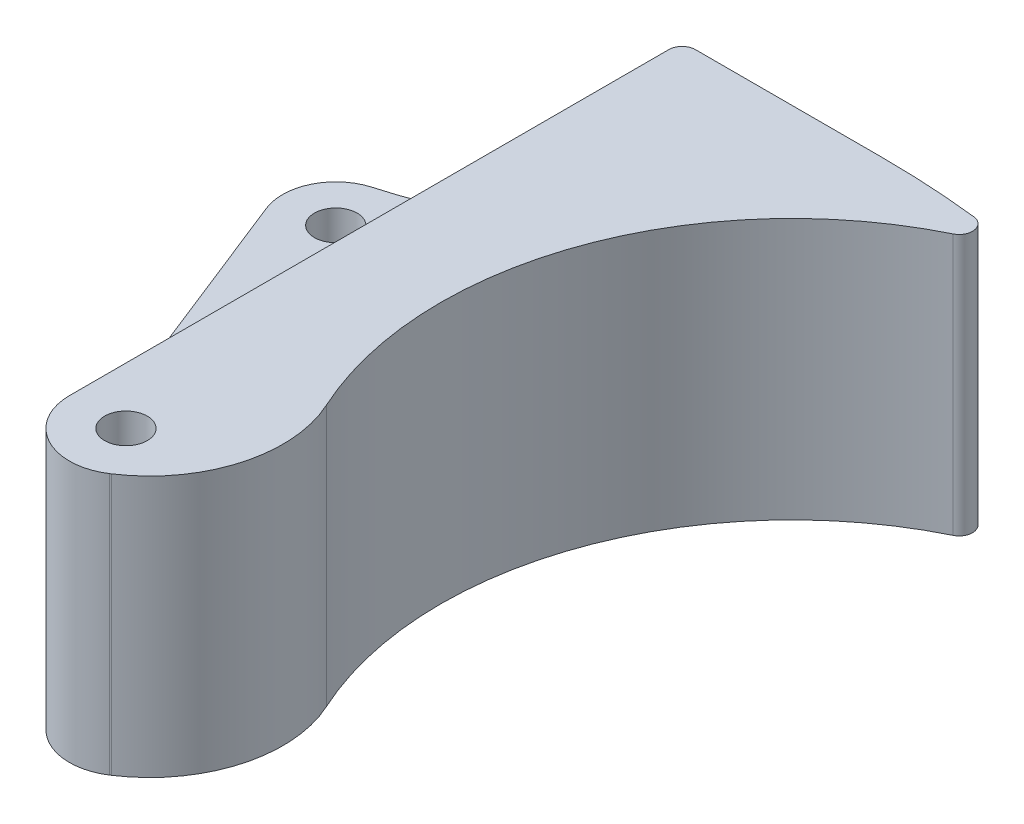
SolidWorks part; units mm, degrees
ref_plane "Front Plane" through (0, 0, 0) normal (0, 0, 1) x (1, 0, 0)
ref_plane "Top Plane" through (0, 0, 0) normal (0, 1, 0) x (1, 0, 0)
ref_plane "Right Plane" through (0, 0, 0) normal (1, 0, 0) x (0, 0, -1)
sketch "Sketch1" plane through (0, 0, 0) normal (0, 1, 0) x (1, 0, 0)
  line L3 (2.9609, -4.5129) -> (13.6525, 2.502)
  line L4 (-5.3975, 58.42) -> (13.6525, 58.42)
  line L6 (-5.3975, 58.42) -> (-5.3975, 0)
  circle A0 centre (0, 0) radius 2.032
  arc A2 (-5.3975, 0) -> (2.9609, -4.5129) centre (0, 0) ccw
  arc A4 (27.6225, 57.2154) -> (13.6525, 58.42) centre (13.6525, -23.19) ccw
  arc A5 (27.6225, 57.2154) -> (13.6525, 2.502) centre (38.1, 25.4) ccw
  dimension "D1" = 66.9925
  dimension "D2" = 4.064
  dimension "D3" = 10.795
  dimension "D4" = 13.97
  dimension "D5" = 58.42
  dimension "D6" = 38.1
  dimension "D7" = 25.4
  dimension "D9" = 19.05
extrude "Boss-Extrude1" add sketch "Sketch1" along normal mid plane 24.892
fillet "Fillet2" radius 12.7 1 edges at (13.6525, 0, -2.502)
sketch "Sketch2" plane through (0, 0, 0) normal (0, 1, 0) x (1, 0, 0)
  line L0 (-5.3975, 40.64) -> (-14.4921, 37.8813)
  line L1 (-5.3975, 58.42) -> (-5.3975, 0) construction
  line L2 (-5.3975, 0) -> (-17.7402, 31.1486)
  line L4 (-5.3975, 40.64) -> (-5.3975, 0)
  arc A0 (-14.4921, 37.8813) -> (-17.7402, 31.1486) centre (-13.0175, 33.02) ccw
  circle A1 centre (-13.0175, 33.02) radius 2.032
  dimension "D1" = 4.064
  dimension "D2" = 5.08
  dimension "D3" = 40.64
  dimension "D4" = 7.62
  dimension "D5" = 7.62
extrude "Boss-Extrude2" add sketch "Sketch2" along normal mid plane 12.3825
fillet "Fillet7" radius 10.16 1 edges at (-5.3975, 0, -40.64)
sketch "Sketch5" [suppressed] plane through (0, 0, -57.15) normal (0, 0, -1) x (-1, 0, 0)
  circle A0 centre (0, 0) radius 1.905
  dimension "D1" = 3.81
extrude "Cut-Extrude3" [suppressed] cut sketch "Sketch5" against normal blind 38.1
fillet "Fillet8" radius 1.27 2 edges at (-5.3975, 0, -58.42) (27.6225, 0, -57.2154)
